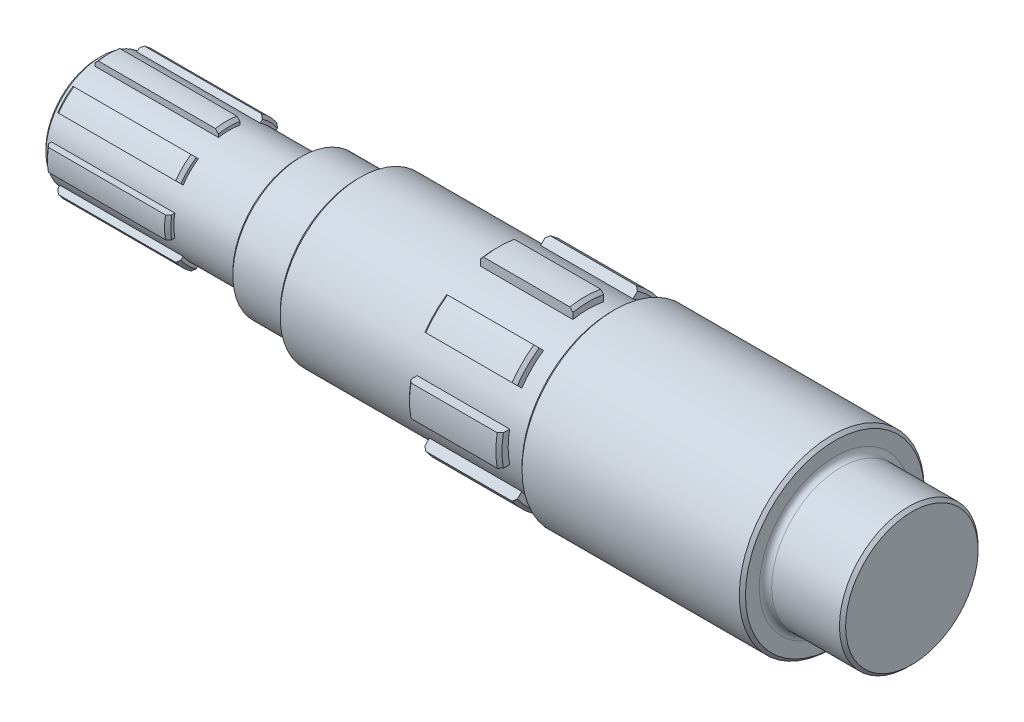
SolidWorks part; units mm, degrees
ref_plane "Front Plane" through (0, 0, 0) normal (0, 0, 1) x (1, 0, 0)
ref_plane "Top Plane" through (0, 0, 0) normal (0, 1, 0) x (1, 0, 0)
ref_plane "Right Plane" through (0, 0, 0) normal (1, 0, 0) x (0, 0, -1)
sketch "Sketch1" plane through (0, 0, 0) normal (0, 0, 1) x (1, 0, 0)
  line L0 (-155.9565, 0) -> (190.3478, 0) construction
  line L1 (-90.9565, 18) -> (-90.9565, 22.3478)
  line L2 (-90.9565, 22.3478) -> (-71.9565, 22.3478)
  line L3 (-71.9565, 22.3478) -> (-71.9565, 26)
  line L4 (-71.9565, 26) -> (-26.9565, 26)
  line L5 (10.5435, 26) -> (10.5435, 30)
  line L6 (10.5435, 30) -> (83.0435, 30)
  line L7 (83.0435, 30) -> (83.0435, 22.5)
  line L8 (83.0435, 22.5) -> (108.0435, 22.5)
  line L9 (108.0435, 22.5) -> (108.0435, 0)
  line L10 (-26.9565, 26) -> (-26.9565, 29)
  line L11 (-26.9565, 29) -> (3.0435, 29)
  line L12 (3.0435, 29) -> (3.0435, 26)
  line L13 (3.0435, 26) -> (10.5435, 26)
  line L14 (-90.9565, 18) -> (-113.4565, 18)
  line L15 (-155.9565, 18) -> (-155.9565, 0)
  line L16 (-155.9565, 0) -> (108.0435, 0)
  line L17 (-153.4565, 18) -> (-153.4565, 20)
  line L18 (-153.4565, 20) -> (-113.4565, 20)
  line L19 (-113.4565, 20) -> (-113.4565, 18)
  line L20 (-153.4565, 18) -> (-155.9565, 18)
  point P3 (-133.4565, 18)
  point P11 (-11.9565, 26)
  point P19 (-155.9565, 75.4675)
  dimension "D2" = 19
  dimension "D3" = 82.5
  dimension "D4" = 72.5
  dimension "D5" = 25
  dimension "D6" = 52
  dimension "D7" = 60
  dimension "D8" = 45
  dimension "D9" = 60
  dimension "D10" = 15
  dimension "D11" = 30
  dimension "D12" = 58
  dimension "D13" = 65
  dimension "D14" = 36
  dimension "D15" = 2.5
  dimension "D16" = 20
  dimension "D17" = 40
  dimension "D18" = 20
revolve "Revolve1" add sketch "Sketch1" angle 360 about L0
chamfer "Chamfer1" distance 1 angle 45 10 edges at (108.0435, 0, 22.5) (83.0435, 0, 30) (10.5435, 0, 30) (3.0435, 0, 29) (-26.9565, 0, 29) (-71.9565, 0, 26) (-90.9565, 0, 22.3478) (-113.4565, 0, 20) (-153.4565, 0, 20) (-155.9565, 0, 18)
sketch "Sketch2" plane through (-153.4565, 0, 0) normal (-1, 0, 0) x (0, 0, 1)
  line L0 (0, 0) -> (0, 34.2808) construction
  line L1 (-3.5, 19.6914) -> (-3.5, 17.6564)
  line L2 (3.5, 19.6914) -> (3.5, 17.6564)
  line L3 (16.3988, 11.449) -> (14.9599, 10.0101)
  line L4 (11.449, 16.3988) -> (10.0101, 14.9599)
  line L5 (19.6914, -3.5) -> (17.6564, -3.5)
  line L6 (19.6914, 3.5) -> (17.6564, 3.5)
  line L7 (11.449, -16.3988) -> (10.0101, -14.9599)
  line L8 (16.3988, -11.449) -> (14.9599, -10.0101)
  line L9 (-3.5, -19.6914) -> (-3.5, -17.6564)
  line L10 (3.5, -19.6914) -> (3.5, -17.6564)
  line L11 (-16.3988, -11.449) -> (-14.9599, -10.0101)
  line L12 (-11.449, -16.3988) -> (-10.0101, -14.9599)
  line L13 (-19.6914, 3.5) -> (-17.6564, 3.5)
  line L14 (-19.6914, -3.5) -> (-17.6564, -3.5)
  line L15 (-11.449, 16.3988) -> (-10.0101, 14.9599)
  line L16 (-16.3988, 11.449) -> (-14.9599, 10.0101)
  circle A0 centre (0, 0) radius 20 construction
  circle A1 centre (0, 0) radius 18 construction
  arc A2 (-3.5, 19.6914) -> (-11.449, 16.3988) centre (0, 0) ccw
  arc A3 (-3.5, 17.6564) -> (-10.0101, 14.9599) centre (0, 0) ccw
  arc A4 (11.449, 16.3988) -> (3.5, 19.6914) centre (0, 0) ccw
  arc A5 (10.0101, 14.9599) -> (3.5, 17.6564) centre (0, 0) ccw
  arc A6 (-16.3988, 11.449) -> (-19.6914, 3.5) centre (0, 0) ccw
  arc A7 (-14.9599, 10.0101) -> (-17.6564, 3.5) centre (0, 0) ccw
  arc A8 (-19.6914, -3.5) -> (-16.3988, -11.449) centre (0, 0) ccw
  arc A9 (-17.6564, -3.5) -> (-14.9599, -10.0101) centre (0, 0) ccw
  arc A10 (-11.449, -16.3988) -> (-3.5, -19.6914) centre (0, 0) ccw
  arc A11 (-10.0101, -14.9599) -> (-3.5, -17.6564) centre (0, 0) ccw
  arc A12 (3.5, -19.6914) -> (11.449, -16.3988) centre (0, 0) ccw
  arc A13 (3.5, -17.6564) -> (10.0101, -14.9599) centre (0, 0) ccw
  arc A14 (16.3988, -11.449) -> (19.6914, -3.5) centre (0, 0) ccw
  arc A15 (14.9599, -10.0101) -> (17.6564, -3.5) centre (0, 0) ccw
  arc A16 (19.6914, 3.5) -> (16.3988, 11.449) centre (0, 0) ccw
  arc A17 (17.6564, 3.5) -> (14.9599, 10.0101) centre (0, 0) ccw
  point P41 (0, 0)
  dimension "D1" = 3.5
  dimension "D2" = 8
extrude "Cut-Extrude1" cut sketch "Sketch2" against normal up to surface (40 mm away) up to face at (-113.4565, 0, 19)
sketch "Sketch3" plane through (-26.9565, 0, 0) normal (-1, 0, 0) x (0, 0, 1)
  line L0 (0, 0) -> (0, 40.4461) construction
  line L1 (-5, 28.5657) -> (-5, 25.5147)
  line L2 (5, 28.5657) -> (5, 25.5147)
  line L3 (16.6635, 23.7345) -> (14.5061, 21.5772)
  line L4 (23.7345, 16.6635) -> (21.5772, 14.5061)
  line L5 (28.5657, 5) -> (25.5147, 5)
  line L6 (28.5657, -5) -> (25.5147, -5)
  line L7 (23.7345, -16.6635) -> (21.5772, -14.5061)
  line L8 (16.6635, -23.7345) -> (14.5061, -21.5772)
  line L9 (5, -28.5657) -> (5, -25.5147)
  line L10 (-5, -28.5657) -> (-5, -25.5147)
  line L11 (-16.6635, -23.7345) -> (-14.5061, -21.5772)
  line L12 (-23.7345, -16.6635) -> (-21.5772, -14.5061)
  line L13 (-28.5657, -5) -> (-25.5147, -5)
  line L14 (-28.5657, 5) -> (-25.5147, 5)
  line L15 (-23.7345, 16.6635) -> (-21.5772, 14.5061)
  line L16 (-16.6635, 23.7345) -> (-14.5061, 21.5772)
  circle A0 centre (0, 0) radius 26 construction
  circle A1 centre (0, 0) radius 29 construction
  arc A2 (-5, 25.5147) -> (-14.5061, 21.5772) centre (0, 0) ccw
  arc A3 (-5, 28.5657) -> (-16.6635, 23.7345) centre (0, 0) ccw
  arc A4 (16.6635, 23.7345) -> (5, 28.5657) centre (0, 0) ccw
  arc A5 (14.5061, 21.5772) -> (5, 25.5147) centre (0, 0) ccw
  arc A6 (28.5657, 5) -> (23.7345, 16.6635) centre (0, 0) ccw
  arc A7 (25.5147, 5) -> (21.5772, 14.5061) centre (0, 0) ccw
  arc A8 (23.7345, -16.6635) -> (28.5657, -5) centre (0, 0) ccw
  arc A9 (21.5772, -14.5061) -> (25.5147, -5) centre (0, 0) ccw
  arc A10 (5, -28.5657) -> (16.6635, -23.7345) centre (0, 0) ccw
  arc A11 (5, -25.5147) -> (14.5061, -21.5772) centre (0, 0) ccw
  arc A12 (-16.6635, -23.7345) -> (-5, -28.5657) centre (0, 0) ccw
  arc A13 (-14.5061, -21.5772) -> (-5, -25.5147) centre (0, 0) ccw
  arc A14 (-28.5657, -5) -> (-23.7345, -16.6635) centre (0, 0) ccw
  arc A15 (-25.5147, -5) -> (-21.5772, -14.5061) centre (0, 0) ccw
  arc A16 (-23.7345, 16.6635) -> (-28.5657, 5) centre (0, 0) ccw
  arc A17 (-21.5772, 14.5061) -> (-25.5147, 5) centre (0, 0) ccw
  point P41 (0, 0)
  dimension "D1" = 5
  dimension "D2" = 8
extrude "Cut-Extrude2" cut sketch "Sketch3" against normal up to surface (30 mm away) up to face at (3.0435, 0, 28)
fillet "Fillet1" radius 2 4 edges at (83.0435, 0, 22.5) (10.5435, 0, 26) (-71.9565, 0, 22.3478) (-90.9565, 0, 18)
